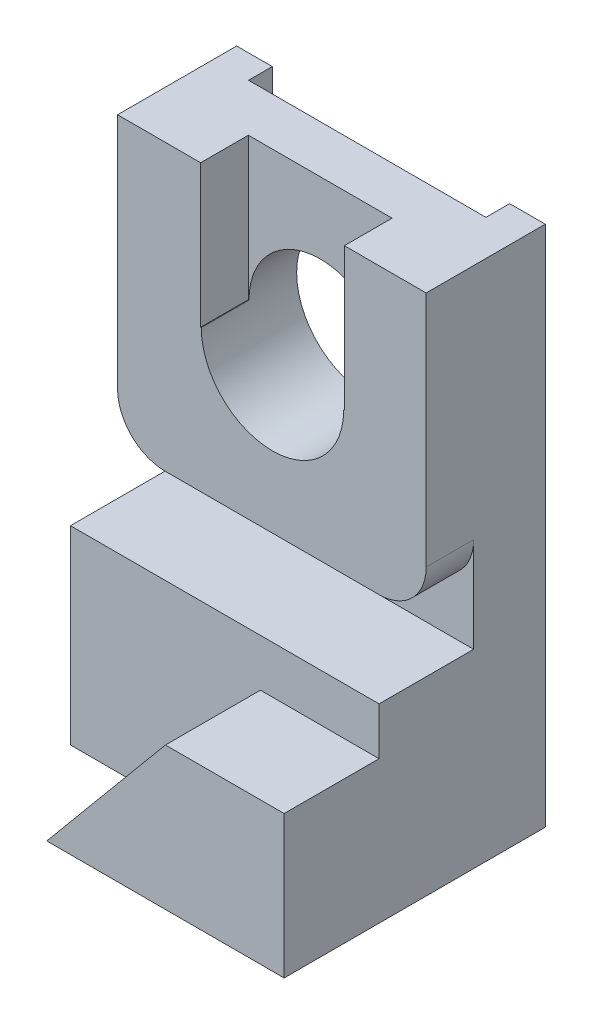
SolidWorks part; units mm, degrees
ref_plane "Plano frontal" through (0, 0, 0) normal (0, 0, 1) x (1, 0, 0)
ref_plane "Plano superior" through (0, 0, 0) normal (0, 1, 0) x (1, 0, 0)
ref_plane "Plano direito" through (0, 0, 0) normal (1, 0, 0) x (0, 0, -1)
sketch "Esboço1" plane through (0, 0, 0) normal (0, 0, 1) x (1, 0, 0)
  line L1 (0, 0) -> (130, 0)
  line L2 (0, 0) -> (0, 80)
  line L3 (0, 80) -> (130, 80)
  line L4 (130, 0) -> (130, 80)
  dimension "D1" = 80
  dimension "D2" = 130
extrude "Ressalto-extrusão1" add sketch "Esboço1" along normal blind 70
sketch "Esboço2" plane through (0, 0, 70) normal (0, 0, 1) x (1, 0, 0)
  line L0 (130, 0) -> (30, 0)
  line L1 (0, 0) -> (130, 0) construction
  line L2 (130, 0) -> (130, 60.0008)
  line L3 (130, 0) -> (130, 80) construction
  line L4 (130, 60.0008) -> (80, 60.0008)
  line L5 (80, 60.0008) -> (30, 0)
  dimension "D1" = 50
  dimension "D2" = 60.0008
  dimension "D3" = 100
extrude "Ressalto-extrusão2" add sketch "Esboço2" along normal blind 40
sketch "Esboço3" plane through (0, 80, 0) normal (0, 1, 0) x (1, 0, 0)
  line L0 (130, -70) -> (130, 0) construction
  line L1 (0, 0) -> (130, 0)
  line L2 (0, 0) -> (0, -30.1683)
  line L3 (0, -30.1683) -> (130, -30.1683)
  line L4 (130, 0) -> (130, -30.1683)
extrude "Ressalto-extrusão3" add sketch "Esboço3" along normal blind 140
sketch "Esboço4" plane through (0, 0, 30.1683) normal (0, 0, 1) x (1, 0, 0)
  line L0 (0, 220) -> (0, 80) construction
  line L1 (130, 220) -> (0, 220)
  line L2 (130, 220) -> (130, 100)
  line L3 (130, 100) -> (0, 100)
  line L4 (0, 220) -> (0, 100)
extrude "Ressalto-extrusão4" add sketch "Esboço4" along normal blind 20
sketch "Esboço5" plane through (0, 220, 0) normal (0, 1, 0) x (1, 0, 0)
  line L4 (15, 0) -> (15, -10)
  line L5 (15, 0) -> (115, 0)
  line L7 (15, -10) -> (115, -10)
  line L8 (115, 0) -> (115, -10)
extrude "Corte-extrusão1" cut sketch "Esboço5" against normal blind 260
fillet "Filete3" radius 20 1 edges at (0, 100, 40.1683)
fillet "Filete4" radius 20 1 edges at (130, 100, 40.1683)
sketch "Esboço12" plane through (0, 220, 0) normal (0, 1, 0) x (1, 0, 0)
  line L0 (130, -50.1683) -> (0, -50.1683) construction
  line L4 (35, -30.0841) -> (35, -50.1683)
  line L6 (35, -50.1683) -> (95.5384, -50.1683)
  line L8 (35, -30.0841) -> (95.5384, -30.0841)
  line L9 (95.5384, -50.1683) -> (95.5384, -30.0841)
extrude "Corte-extrusão3" cut sketch "Esboço12" against normal blind 60
sketch "Esboço13" plane through (0, 0, 50.1683) normal (0, 0, 1) x (1, 0, 0)
  line L0 (35, 160) -> (95.5384, 160) construction
  circle A0 centre (65.2692, 160) radius 30
extrude "Corte-extrusão4" cut sketch "Esboço13" against normal blind 60
